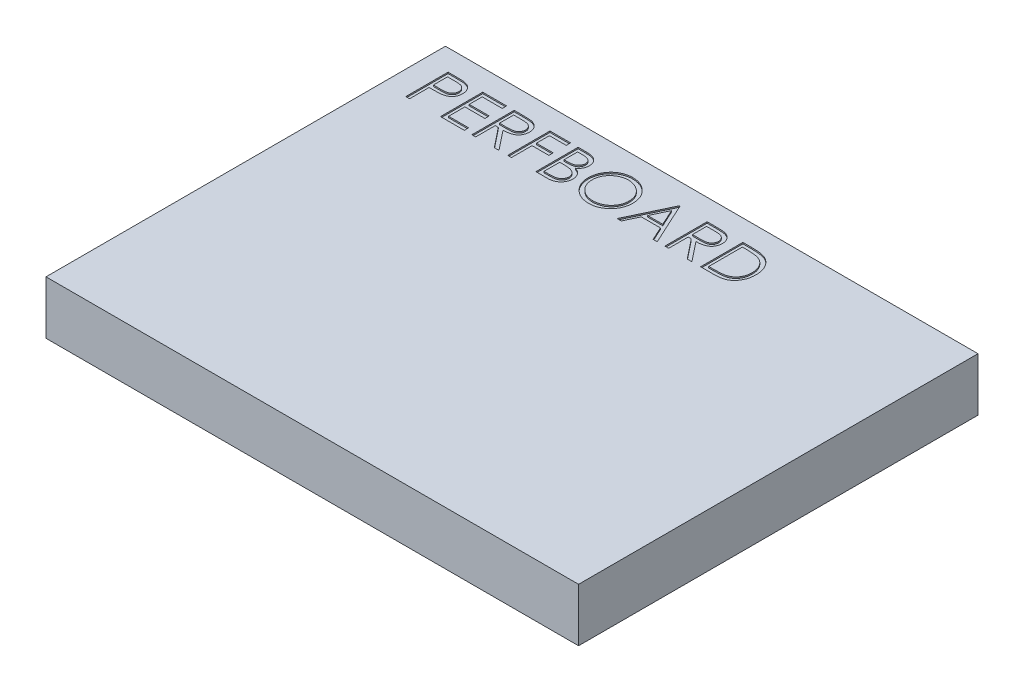
SolidWorks part; units mm, degrees
ref_plane "Front Plane" through (0, 0, 0) normal (0, 0, 1) x (1, 0, 0)
ref_plane "Top Plane" through (0, 0, 0) normal (0, 1, 0) x (1, 0, 0)
ref_plane "Right Plane" through (0, 0, 0) normal (1, 0, 0) x (0, 0, -1)
sketch "Sketch1" plane through (0, 0, 0) normal (0, 1, 0) x (1, 0, 0)
  line L1 (-20, -15) -> (20, -15)
  line L2 (-20, -15) -> (-20, 15)
  line L3 (-20, 15) -> (20, 15)
  line L4 (20, -15) -> (20, 15)
  line L5 (-20, -15) -> (20, 15) construction
  line L6 (-20, 15) -> (20, -15) construction
  point P0 (0, 0)
  dimension "D1" = 40
  dimension "D2" = 30
extrude "Boss-Extrude1" add sketch "Sketch1" along normal blind 4
sketch "Sketch2" plane through (0, 4, 0) normal (0, 1, 0) x (1, 0, 0)
  text T0 "PERFBOARD" font "Century Gothic" height 3.175
extrude "Cut-Extrude1" cut sketch "Sketch2" against normal blind 0.1
